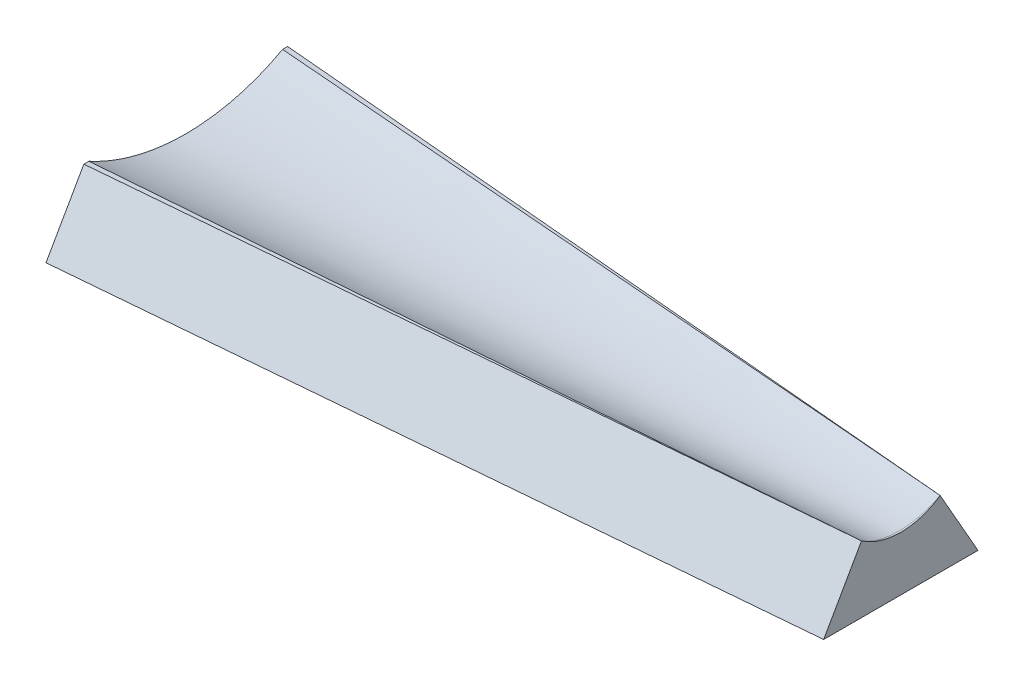
SolidWorks part; units mm, degrees
ref_plane "Front Plane" through (0, 0, 0) normal (0, 0, 1) x (1, 0, 0)
ref_plane "Top Plane" through (0, 0, 0) normal (0, 1, 0) x (1, 0, 0)
ref_plane "Right Plane" through (0, 0, 0) normal (1, 0, 0) x (0, 0, -1)
sketch "Sketch1" plane through (0, 0, 0) normal (0, 1, 0) x (1, 0, 0)
  line L0 (0, 0) -> (203.2, 17.7777)
  line L1 (203.2, 17.7777) -> (203.2, 40.1297)
  line L2 (203.2, 40.1297) -> (0, 57.9074)
  line L3 (0, 57.9074) -> (0, 0)
  line L4 (203.2, 40.1297) -> (0, 40.1297) construction
  line L5 (203.2, 17.7777) -> (0, 17.7777) construction
  line L6 (0, 28.9537) -> (203.2, 28.9537) construction
  dimension "JISW" = 22.352
  dimension "Cut To Length" = 203.2
  dimension "Crosscut Angle" = 5
extrude "Boss-Extrude1" add sketch "Sketch1" against normal blind 19.05 draft 29.55 draft outward yes
sketch "Sketch2" plane through (0, 0, 0) normal (0, 0, 1) x (1, 0, 0)
  line L0 (0, 0) -> (203.2, 0)
  line L1 (0, 0) -> (0, -18.8961)
  line L2 (203.2, 0) -> (203.2, -18.8961)
  line L3 (0, -18.8961) -> (203.2, -18.8961)
extrude "Cut-Extrude1" cut sketch "Sketch2" against normal through all and the other way through all flip side to cut
ref_plane "Plane1" through (197.6647, -33.0777, 0) normal (0.9863, -0.165, 0) x (0, 0, -1)
sketch "Sketch4" plane through (197.6647, -33.0777, 0) normal (0.9863, -0.165, 0) x (0, 0, -1)
  line L0 (28.9537, 33.5377) -> (28.9537, 49.4127) construction
  line L1 (17.7777, 33.5377) -> (40.1297, 33.5377) construction
  circle A0 centre (28.9537, 49.4127) radius 19.4144
  dimension "InRadius" = 15.875
extrude "Cut-Extrude2" cut sketch "Sketch4" against normal through all draft 10.5 and the other way through all draft 9.5
